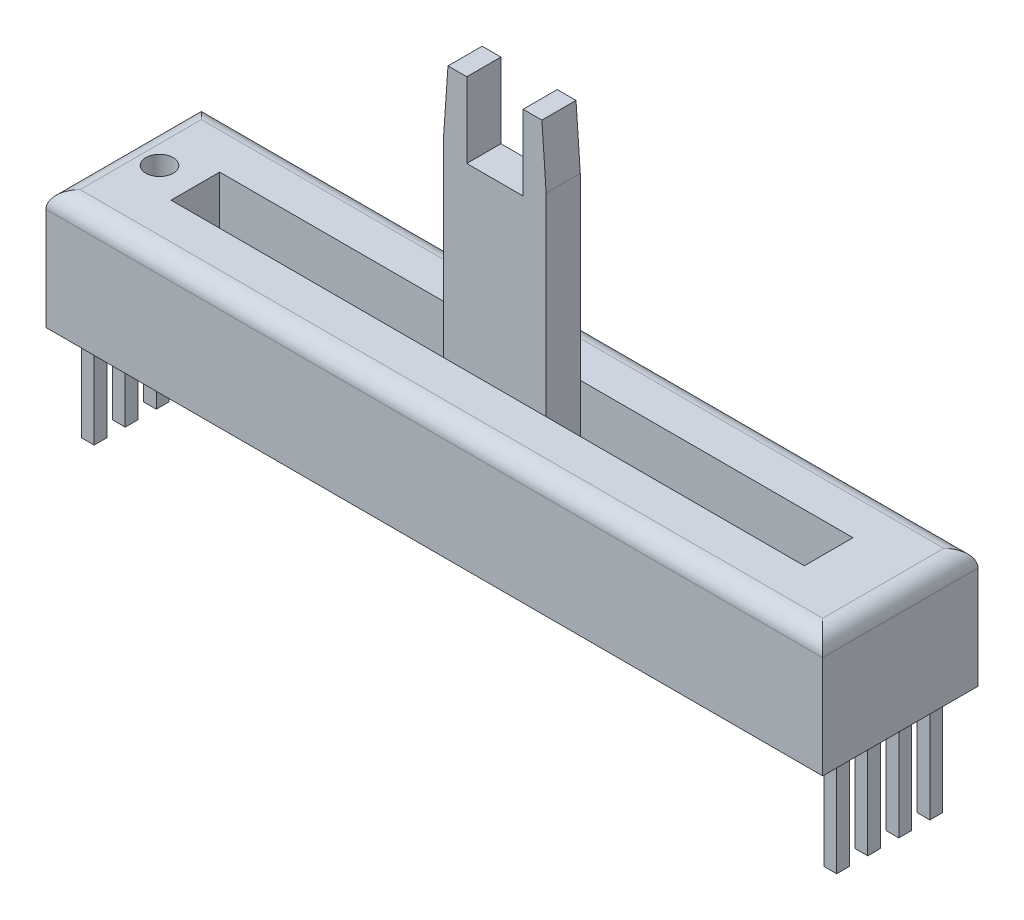
SolidWorks part; units mm, degrees
ref_plane "Front Plane" through (0, 0, 0) normal (0, 0, 1) x (1, 0, 0)
ref_plane "Top Plane" through (0, 0, 0) normal (0, 1, 0) x (1, 0, 0)
ref_plane "Right Plane" through (0, 0, 0) normal (1, 0, 0) x (0, 0, -1)
sketch "Sketch1" plane through (0, 0, 0) normal (0, 1, 0) x (1, 0, 0)
  line L1 (-22.75, -4.55) -> (22.75, -4.55)
  line L2 (-22.75, -4.55) -> (-22.75, 4.55)
  line L3 (-22.75, 4.55) -> (22.75, 4.55)
  line L4 (22.75, -4.55) -> (22.75, 4.55)
  line L5 (-22.75, -4.55) -> (22.75, 4.55) construction
  line L6 (-22.75, 4.55) -> (22.75, -4.55) construction
  point P0 (0, 0)
  dimension "D1" = 9.1
  dimension "D2" = 45.5
extrude "Boss-Extrude1" add sketch "Sketch1" along normal blind 7
sketch "Sketch2" plane through (0, 7, 0) normal (0, 1, 0) x (1, 0, 0)
  line L1 (-18.55, -1.425) -> (18.55, -1.425)
  line L2 (-18.55, -1.425) -> (-18.55, 1.425)
  line L3 (-18.55, 1.425) -> (18.55, 1.425)
  line L4 (18.55, -1.425) -> (18.55, 1.425)
  line L5 (-18.55, -1.425) -> (18.55, 1.425) construction
  line L6 (-18.55, 1.425) -> (18.55, -1.425) construction
  point P0 (0, 0)
  dimension "D1" = 2.85
  dimension "D2" = 37.1
extrude "Cut-Extrude1" cut sketch "Sketch2" against normal blind 5
sketch "Sketch3" plane through (0, 7, 0) normal (0, 1, 0) x (1, 0, 0)
  line L0 (-15.125, 0) -> (15.125, 0) construction
  line L1 (-22.75, 0) -> (-18.55, 0) construction
  line L2 (-22.75, 4.55) -> (-22.75, -4.55) construction
  line L3 (-18.55, 1.425) -> (-18.55, -1.425) construction
  circle A0 centre (-20.65, 0) radius 0.8
  point P9 (-20.65, 0)
  dimension "D1" = 1.6
extrude "Cut-Extrude2" cut sketch "Sketch3" against normal blind 5
fillet "Fillet1" radius 1 4 edges at (0, 7, -4.55) (0, 7, 4.55) (-22.75, 7, 0) (22.75, 7, 0)
sketch "Sketch4" plane through (0, 0, 0) normal (0, -1, 0) x (1, 0, 0)
  line L0 (-21.75, 4.55) -> (-21.75, 2.73) construction
  line L1 (-22.75, 4.55) -> (22.75, 4.55) construction
  line L2 (-21.75, 2.73) -> (-21.75, 0.91) construction
  line L3 (-21.75, 0.91) -> (-21.75, -0.91) construction
  line L4 (-21.75, -0.91) -> (-21.75, -2.73) construction
  line L5 (-21.75, -2.73) -> (-21.75, -4.55) construction
  line L6 (22.75, -4.55) -> (-22.75, -4.55) construction
  line L7 (-22.75, -4.55) -> (-22.75, 4.55) construction
  line L9 (-22.125, 2.355) -> (-21.375, 2.355)
  line L10 (-22.125, 2.355) -> (-22.125, 3.105)
  line L11 (-22.125, 3.105) -> (-21.375, 3.105)
  line L12 (-21.375, 2.355) -> (-21.375, 3.105)
  line L13 (-22.125, 2.355) -> (-21.375, 3.105) construction
  line L14 (-22.125, 3.105) -> (-21.375, 2.355) construction
  line L15 (-22.125, 0.535) -> (-21.375, 0.535)
  line L16 (-22.125, 0.535) -> (-22.125, 1.285)
  line L17 (-22.125, 1.285) -> (-21.375, 1.285)
  line L18 (-21.375, 0.535) -> (-21.375, 1.285)
  line L19 (-22.125, 0.535) -> (-21.375, 1.285) construction
  line L20 (-22.125, 1.285) -> (-21.375, 0.535) construction
  line L21 (-22.125, -1.285) -> (-21.375, -1.285)
  line L22 (-22.125, -1.285) -> (-22.125, -0.535)
  line L23 (-22.125, -0.535) -> (-21.375, -0.535)
  line L24 (-21.375, -1.285) -> (-21.375, -0.535)
  line L25 (-22.125, -1.285) -> (-21.375, -0.535) construction
  line L26 (-22.125, -0.535) -> (-21.375, -1.285) construction
  line L27 (-22.125, -3.105) -> (-21.375, -3.105)
  line L28 (-22.125, -3.105) -> (-22.125, -2.355)
  line L29 (-22.125, -2.355) -> (-21.375, -2.355)
  line L30 (-21.375, -3.105) -> (-21.375, -2.355)
  line L31 (-22.125, -3.105) -> (-21.375, -2.355) construction
  line L32 (-22.125, -2.355) -> (-21.375, -3.105) construction
  dimension "D1" = 0.75
  dimension "D2" = 1
extrude "Boss-Extrude2" add sketch "Sketch4" along normal blind 6 contours L28 L27 L30 L29 | L22 L21 L24 L23 | L16 L15 L18 L17 | L10 L9 L12 L11
mirror "Mirror1" about plane through (0, 0, 0) normal (1, 0, 0) of "Boss-Extrude2"
sketch "Sketch5" plane through (0, 2, 0) normal (0, 1, 0) x (1, 0, 0)
  line L1 (-3, -1) -> (3, -1)
  line L2 (-3, -1) -> (-3, 1)
  line L3 (-3, 1) -> (3, 1)
  line L4 (3, -1) -> (3, 1)
  line L5 (-3, -1) -> (3, 1) construction
  line L6 (-3, 1) -> (3, -1) construction
  point P0 (0, 0)
  dimension "D1" = 6
  dimension "D2" = 2
extrude "Boss-Extrude3" add sketch "Sketch5" along normal offset from surface (19.5 mm away) 21.5 up to face at (-21.75, 0, 2.73)
sketch "Sketch6" plane through (0, 0, 1) normal (0, 0, 1) x (1, 0, 0)
  line L0 (0, -5.005) -> (0, 5.005) construction
  line L1 (-1.65, 17.1) -> (1.65, 17.1)
  line L2 (-1.65, 17.1) -> (-1.65, 21.5)
  line L3 (-1.65, 21.5) -> (1.65, 21.5)
  line L4 (1.65, 17.1) -> (1.65, 21.5)
  line L5 (-1.65, 17.1) -> (1.65, 21.5) construction
  line L6 (-1.65, 21.5) -> (1.65, 17.1) construction
  line L7 (3, 21.5) -> (-3, 21.5) construction
  point P0 (0, 19.3)
  dimension "D1" = 3.3
  dimension "D2" = 4.4
extrude "Cut-Extrude3" cut sketch "Sketch6" against normal up to next
chamfer "Chamfer1" distance 0.25 angle 86 2 edges at (3, 21.5, 0) (-3, 21.5, 0)
